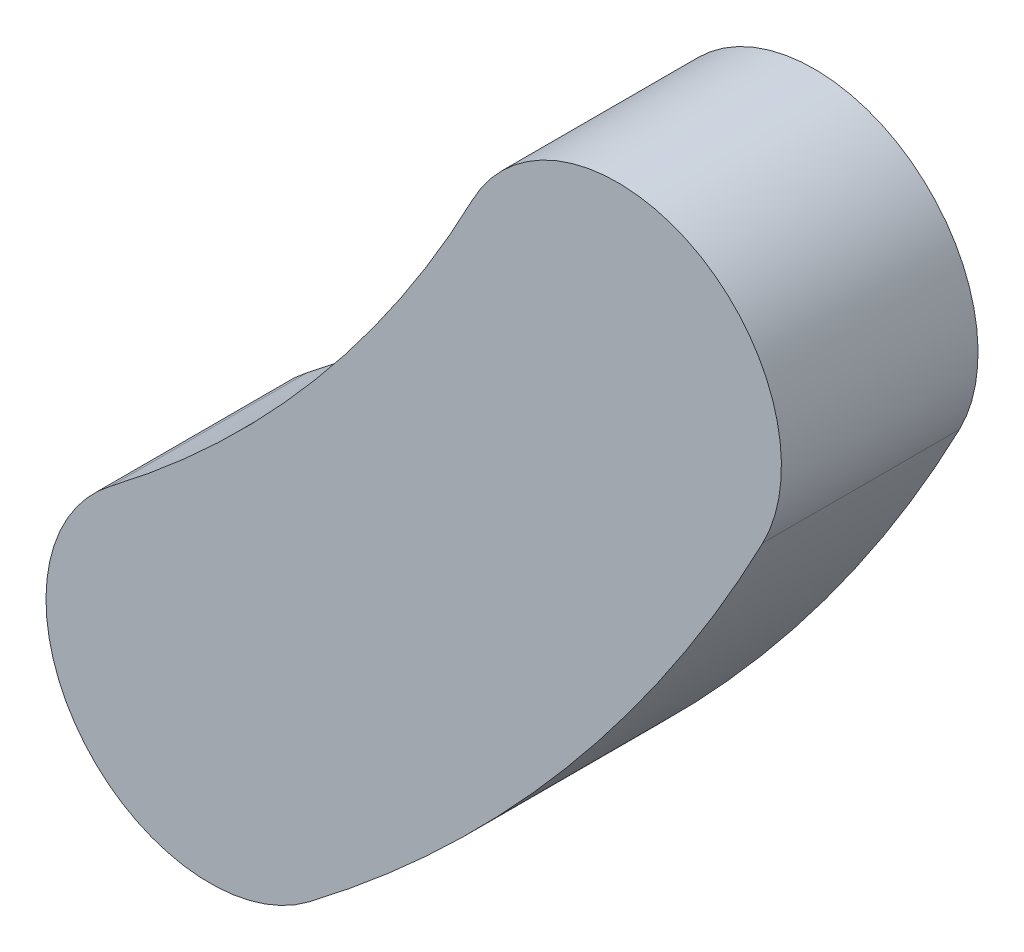
SolidWorks part; units mm, degrees
ref_plane "Front Plane" through (0, 0, 0) normal (0, 0, 1) x (1, 0, 0)
ref_plane "Top Plane" through (0, 0, 0) normal (0, 1, 0) x (1, 0, 0)
ref_plane "Right Plane" through (0, 0, 0) normal (1, 0, 0) x (0, 0, -1)
sketch "Sketch2" plane through (37.1806, 0, 0) normal (0, 0, 1) x (1, 0, 0)
  arc A0 (23.2269, -1.99) -> (29.448, 5.3813) centre (9.8409, 15.6181) ccw construction
  arc A1 (24.7399, -3.9802) -> (31.6641, 4.2242) centre (9.8409, 15.6181) ccw
  arc A2 (21.7139, 0.0002) -> (27.2319, 6.5383) centre (9.8409, 15.6181) ccw
  arc A3 (21.7139, 0.0002) -> (24.7399, -3.9802) centre (23.2269, -1.99) ccw
  arc A4 (31.6641, 4.2242) -> (27.2319, 6.5383) centre (29.448, 5.3813) ccw
  point P3 (26.7442, 1.3524)
  dimension "D1" = 22.1186
  dimension "D2" = 19.6186
extrude "Boss-Extrude1" add sketch "Sketch2" along normal blind 3
